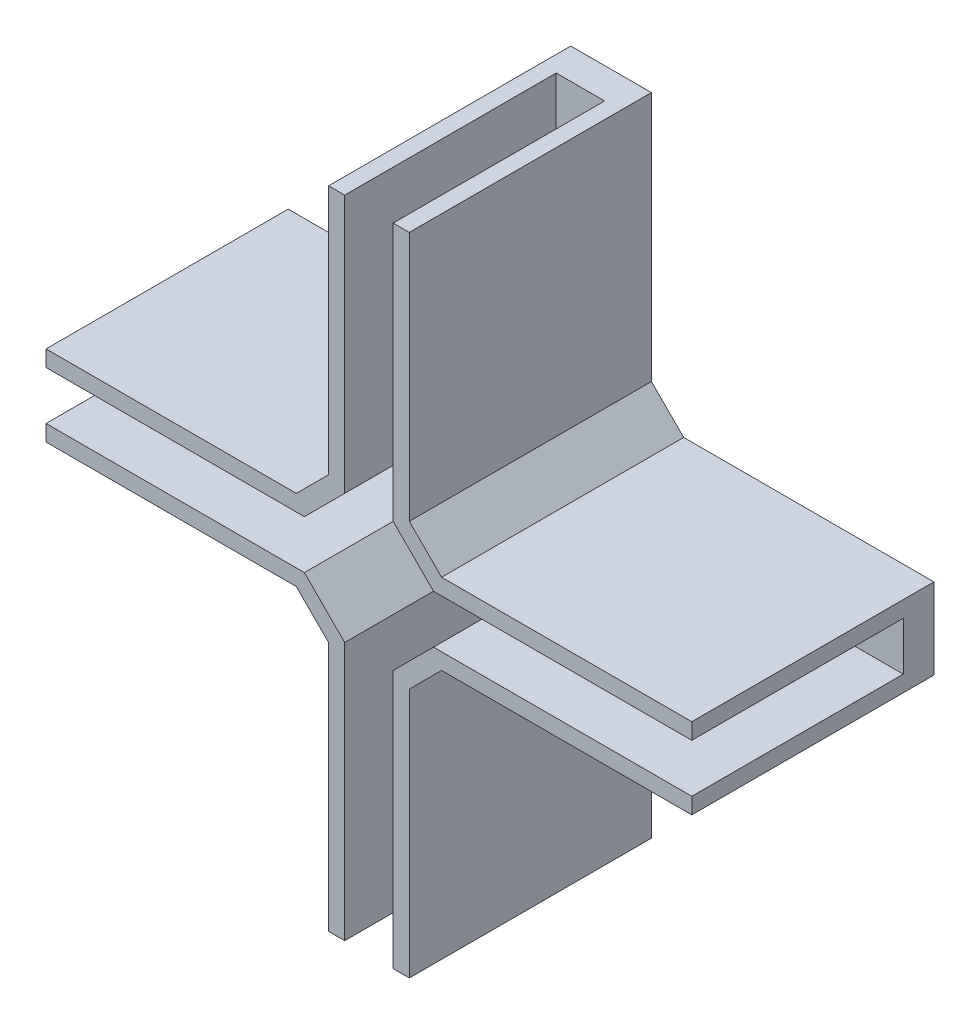
SolidWorks part; units mm, degrees
ref_plane "Plano frontal" through (0, 0, 0) normal (0, 0, 1) x (1, 0, 0)
ref_plane "Plano superior" through (0, 0, 0) normal (0, 1, 0) x (1, 0, 0)
ref_plane "Plano direito" through (0, 0, 0) normal (1, 0, 0) x (0, 0, -1)
sketch "Esboço1" plane through (0, 0, 0) normal (0, 0, 1) x (1, 0, 0)
  line L0 (2.5, 4.5) -> (2.5, 20)
  line L1 (-2.5, -20) -> (2.5, -20)
  line L2 (-2.5, -20) -> (-2.5, -4.5)
  line L3 (-2.5, 20) -> (2.5, 20)
  line L4 (2.5, -20) -> (2.5, -4.5)
  line L5 (-2.5, -20) -> (2.5, 20) construction
  line L6 (-2.5, 20) -> (2.5, -20) construction
  line L7 (-20, -2.5) -> (-4.5, -2.5)
  line L8 (-20, -2.5) -> (-20, 2.5)
  line L9 (-20, 2.5) -> (-4.5, 2.5)
  line L10 (20, -2.5) -> (20, 2.5)
  line L11 (-20, -2.5) -> (20, 2.5) construction
  line L12 (-20, 2.5) -> (20, -2.5) construction
  line L13 (4.5, -2.5) -> (20, -2.5)
  line L14 (4.5, 2.5) -> (20, 2.5)
  line L15 (-2.5, 4.5) -> (-2.5, 20)
  line L16 (-4.5, -2.5) -> (-2.5, -4.5)
  line L17 (-4.5, 2.5) -> (-2.5, 4.5)
  line L18 (4.5, 2.5) -> (2.5, 4.5)
  line L19 (2.5, -4.5) -> (4.5, -2.5)
  point P0 (0, 0)
  point P6 (0, 0)
  point P11 (-2.5, -2.5)
  point P12 (2.5, 2.5)
  point P14 (-2.5, 2.5)
  point P15 (2.5, -2.5)
  dimension "D1" = 40
  dimension "D2" = 5
  dimension "D3" = 40
  dimension "D4" = 5
extrude "Ressalto-extrusão1" add sketch "Esboço1" along normal blind 15 contours L2 L9 L4 L3 | L7 L10 L9 L4 | L9 L2 L7 L4 | L9 L8 L7 L2 | L7 L2 L1 L4
sketch "Esboço2" plane through (0, 0, 15) normal (0, 0, 1) x (1, 0, 0)
  line L0 (-20, -2.5) -> (-20, 2.5) construction
  line L1 (20, -1.5) -> (-20, -1.5)
  line L2 (20, -1.5) -> (20, 1.5)
  line L3 (20, 1.5) -> (-20, 1.5)
  line L4 (-20, -1.5) -> (-20, 1.5)
  line L5 (20, -1.5) -> (-20, 1.5) construction
  line L6 (20, 1.5) -> (-20, -1.5) construction
  line L7 (-2.5, -20) -> (2.5, -20) construction
  line L8 (-1.5, 20) -> (1.5, 20)
  line L9 (-1.5, 20) -> (-1.5, -20)
  line L10 (-1.5, -20) -> (1.5, -20)
  line L11 (1.5, 20) -> (1.5, -20)
  line L12 (-1.5, 20) -> (1.5, -20) construction
  line L13 (-1.5, -20) -> (1.5, 20) construction
  point P0 (0, 0)
  point P8 (0, 0)
  dimension "D1" = 3
  dimension "D2" = 3
extrude "Corte-extrusão1" cut sketch "Esboço2" against normal blind 13.1 contours L1 L4 L3 L2 | L11 L10 L9 L8
chamfer "Chanfro1" [suppressed] distance 0.5 angle 45
fillet "Filete2" [suppressed] radius 0.75
chamfer "Chanfro2" distance 2.5 angle 45 4 edges at (1.5, -1.5, 8.45) (1.5, 1.5, 8.45) (-1.5, 1.5, 8.45) (-1.5, -1.5, 8.45)
equation "\"1c\"=15.3402"
